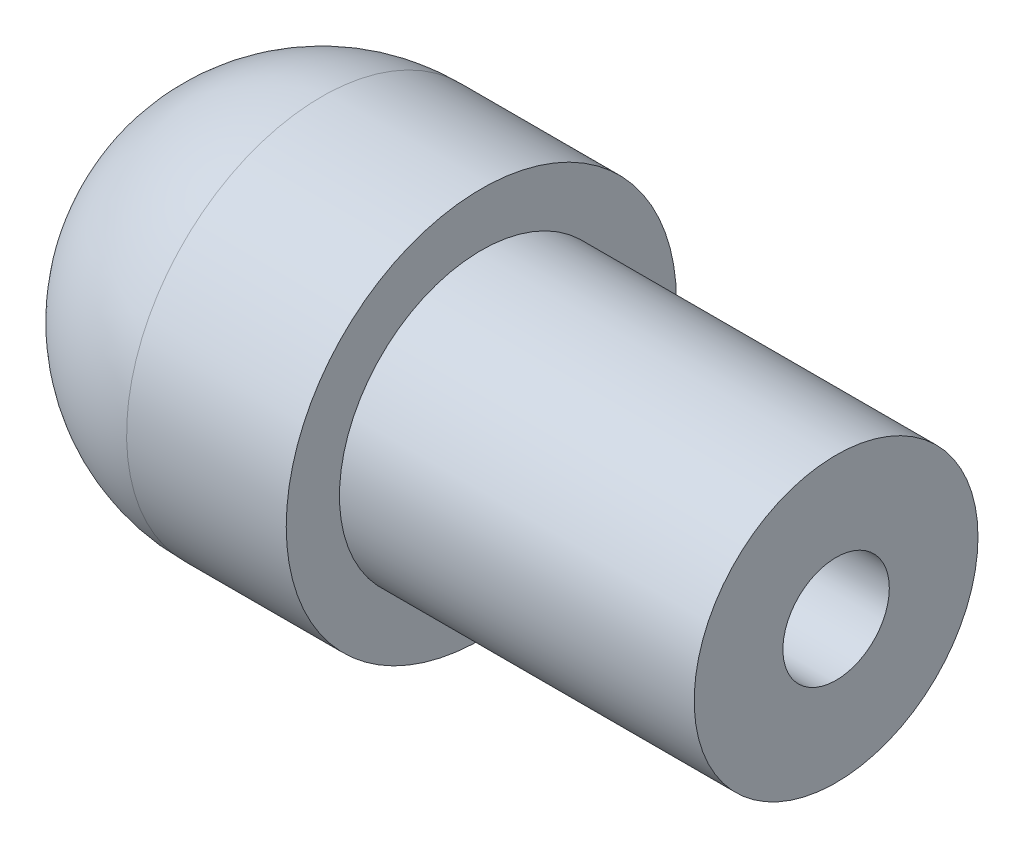
SolidWorks part; units mm, degrees
ref_plane "Front Plane" through (0, 0, 0) normal (0, 0, 1) x (1, 0, 0)
ref_plane "Top Plane" through (0, 0, 0) normal (0, 1, 0) x (1, 0, 0)
ref_plane "Right Plane" through (0, 0, 0) normal (1, 0, 0) x (0, 0, -1)
sketch "Sketch3" plane through (0, 0, 0) normal (0, 0, 1) x (1, 0, 0)
  line L1 (5.5, 5.5) -> (10, 5.5)
  line L2 (10, 5.5) -> (10, 4)
  line L3 (10, 4) -> (20, 4)
  line L4 (20, 4) -> (20, 0)
  line L5 (20, 0) -> (0, 0)
  line L6 (0, 0) -> (0, -5.3827) construction
  line L7 (0, 0) -> (-5.2734, 0) construction
  arc A1 (0, 0) -> (5.5, 5.5) centre (5.5, 0) cw
  point P4 (20, 2)
  dimension "D1" = 5.5
  dimension "D2" = 10
  dimension "D3" = 10
  dimension "D4" = 4
revolve "Revolve1" add sketch "Sketch3" angle 360 about L7
sketch "Sketch4" plane through (20, 0, 0) normal (1, 0, 0) x (0, 0, -1)
  circle A0 centre (0, 0) radius 1.5
  dimension "D1" = 3
extrude "Cut-Extrude1" cut sketch "Sketch4" against normal blind 14.5
